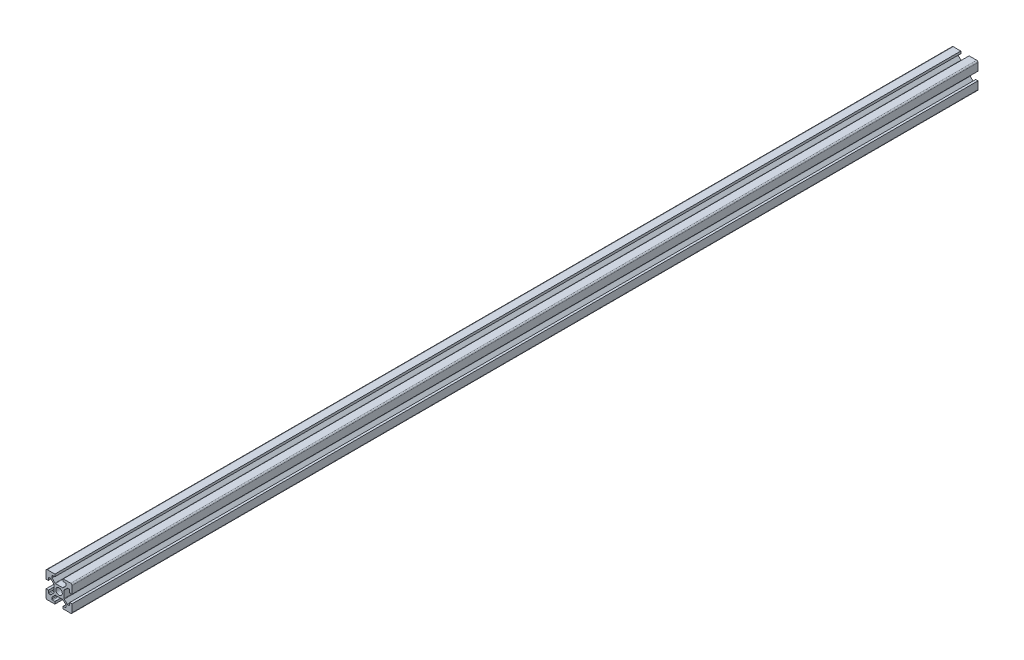
SolidWorks part; units mm, degrees
material "1060 Alloy"
ref_plane "Front Plane" through (0, 0, 0) normal (0, 0, 1) x (1, 0, 0)
ref_plane "Top Plane" through (0, 0, 0) normal (0, 1, 0) x (1, 0, 0)
ref_plane "Right Plane" through (0, 0, 0) normal (1, 0, 0) x (0, 0, -1)
sketch "Sketch1" plane through (0, 0, 0) normal (0, 0, 1) x (1, 0, 0)
  line L0 (20, 0) -> (-8.059, 28.059) construction
  line L1 (0, 0) -> (6.8, 0)
  line L2 (0, 0) -> (0, 6.8)
  line L3 (0, 20) -> (6.8, 20)
  line L4 (20, 0) -> (20, 6.8)
  line L5 (6.8, 20) -> (6.8, 18.2)
  line L6 (20, 20) -> (8.2322, 8.2322) construction
  line L7 (12.95, 6.1) -> (7.05, 6.1)
  line L8 (13.9, 7.05) -> (13.9, 12.95)
  line L9 (12.95, 13.9) -> (7.05, 13.9)
  line L10 (6.1, 7.05) -> (6.1, 12.95)
  line L11 (13.9, 6.1) -> (6.1, 13.9) construction
  line L12 (13.9, 13.9) -> (6.1, 6.1) construction
  line L13 (4.55, 16.4) -> (7.05, 13.9)
  line L14 (13.2, 18.2) -> (13.2, 20)
  line L15 (1.8, 6.8) -> (0, 6.8)
  line L16 (0, 13.2) -> (0, 20)
  line L17 (0, 13.2) -> (1.8, 13.2)
  line L18 (10, 10) -> (10, 13.9) construction
  line L19 (16.4, 4.55) -> (13.9, 7.05)
  line L20 (4.55, 16.4) -> (4.55, 18.2)
  line L21 (4.55, 18.2) -> (6.8, 18.2)
  line L22 (13.2, 18.2) -> (15.45, 18.2)
  line L23 (15.45, 18.2) -> (15.45, 16.4)
  line L24 (15.45, 16.4) -> (12.95, 13.9)
  line L25 (16.4, 4.55) -> (18.2, 4.55)
  line L26 (18.2, 4.55) -> (18.2, 6.8)
  line L27 (20, 6.8) -> (18.2, 6.8)
  line L28 (18.2, 13.2) -> (20, 13.2)
  line L29 (18.2, 13.2) -> (18.2, 15.45)
  line L30 (18.2, 15.45) -> (16.4, 15.45)
  line L31 (16.4, 15.45) -> (13.9, 12.95)
  line L32 (1.8, 4.55) -> (3.6, 4.55)
  line L33 (3.6, 15.45) -> (6.1, 12.95)
  line L34 (3.6, 15.45) -> (1.8, 15.45)
  line L35 (1.8, 15.45) -> (1.8, 13.2)
  line L36 (0, 13.2) -> (1.8, 13.2)
  line L37 (1.8, 6.8) -> (0, 6.8)
  line L38 (3.6, 4.55) -> (6.1, 7.05)
  line L39 (1.8, 6.8) -> (1.8, 4.55)
  line L40 (15.45, 3.6) -> (12.95, 6.1)
  line L41 (4.55, 3.6) -> (7.05, 6.1)
  line L42 (4.55, 1.8) -> (4.55, 3.6)
  line L43 (6.8, 1.8) -> (4.55, 1.8)
  line L44 (6.8, 1.8) -> (6.8, 0)
  line L45 (15.45, 3.6) -> (15.45, 1.8)
  line L46 (15.45, 1.8) -> (13.2, 1.8)
  line L47 (13.2, 0) -> (13.2, 1.8)
  line L48 (13.2, 20) -> (20, 20)
  line L49 (20, 13.2) -> (20, 20)
  line L50 (13.2, 0) -> (20, 0)
  line L51 (6.1, 6.1) -> (-5.5045, -5.5045) construction
  circle A0 centre (10, 10) radius 2.5
  point P25 (10, 16.4)
  point P39 (13.2, 19.1)
  point P46 (0.9, 6.8)
  dimension "D3" = 5
  dimension "D2" = 20
  dimension "D4" = 7.8
  dimension "D5" = 7.8
  dimension "D6" = 6.8
  dimension "D7" = 6.8
  dimension "D8" = 1.8
  dimension "D9" = 10.9
  dimension "D10" = 1.8
  dimension "D11" = 10.9
  dimension "D12" = 20
extrude "Boss-Extrude1" add sketch "Sketch1" along normal blind 695.1 contours L47 L50 L4 L27 L26 L25 L19 L8 L31 L30 L29 L28 L49 L48 L14 L22 L23 L24 L9 L13 L20 L21 L5 L3 L16 L17 L35 L34 L33 L10 L38 L32 L39 L15 L2 L1 L44 L43 L42 L41 L7 L40 L45 L46 A0
fillet "Fillet1" radius 1 4 edges at (20, 20, 347.55) (20, 0, 347.55) (0, 0, 347.55) (0, 20, 347.55)
fillet "Fillet2" radius 0.5 6 edges at (4.55, 18.2, 347.55) (4.55, 16.4, 347.55) (7.05, 13.9, 347.55) (15.45, 18.2, 347.55) (15.45, 16.4, 347.55) (12.95, 13.9, 347.55)
fillet "Fillet3" radius 0.5 6 edges at (18.2, 15.45, 347.55) (16.4, 15.45, 347.55) (13.9, 12.95, 347.55) (18.2, 4.55, 347.55) (13.9, 7.05, 347.55) (16.4, 4.55, 347.55)
fillet "Fillet4" radius 0.5 6 edges at (1.8, 15.45, 347.55) (3.6, 15.45, 347.55) (6.1, 12.95, 347.55) (3.6, 4.55, 347.55) (1.8, 4.55, 347.55) (6.1, 7.05, 347.55)
fillet "Fillet5" radius 0.5 6 edges at (7.05, 6.1, 347.55) (4.55, 3.6, 347.55) (4.55, 1.8, 347.55) (15.45, 1.8, 347.55) (15.45, 3.6, 347.55) (12.95, 6.1, 347.55)
